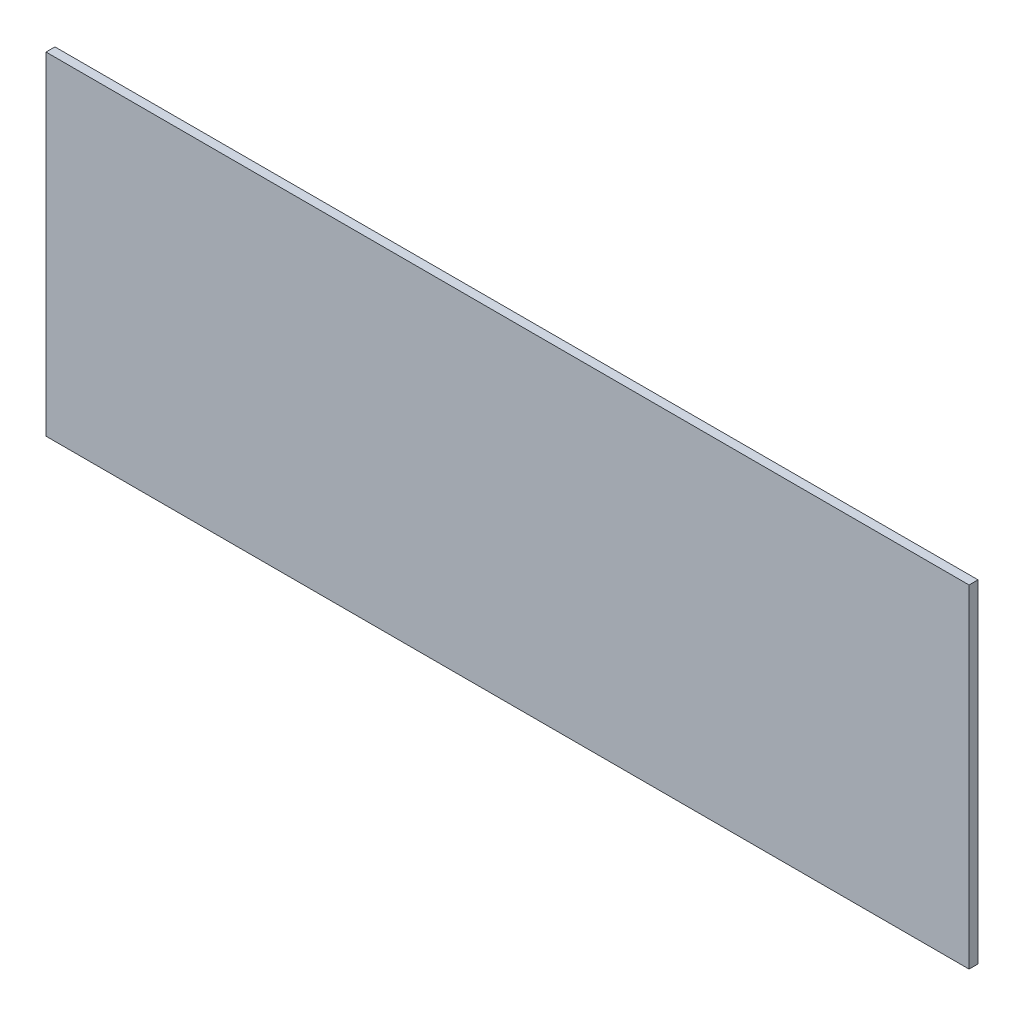
SolidWorks part; units mm, degrees
ref_plane "Front Plane" through (0, 0, 0) normal (0, 0, 1) x (1, 0, 0)
ref_plane "Top Plane" through (0, 0, 0) normal (0, 1, 0) x (1, 0, 0)
ref_plane "Right Plane" through (0, 0, 0) normal (1, 0, 0) x (0, 0, -1)
sketch "Sketch1" plane through (0, 0, 0) normal (0, 0, 1) x (1, 0, 0)
  line L0 (210, 26.0212) -> (210, -9.7253) construction
  line L1 (520, -85.8471) -> (210, -85.8471)
  line L2 (520, -85.8471) -> (520, 25.8895)
  line L3 (520, 25.8895) -> (210, 25.8895)
  line L4 (210, -85.8471) -> (210, 25.8895)
  line L5 (500, 25.8895) -> (0, 25.8895) construction
extrude "Boss-Extrude1" add sketch "Sketch1" along normal blind 3
